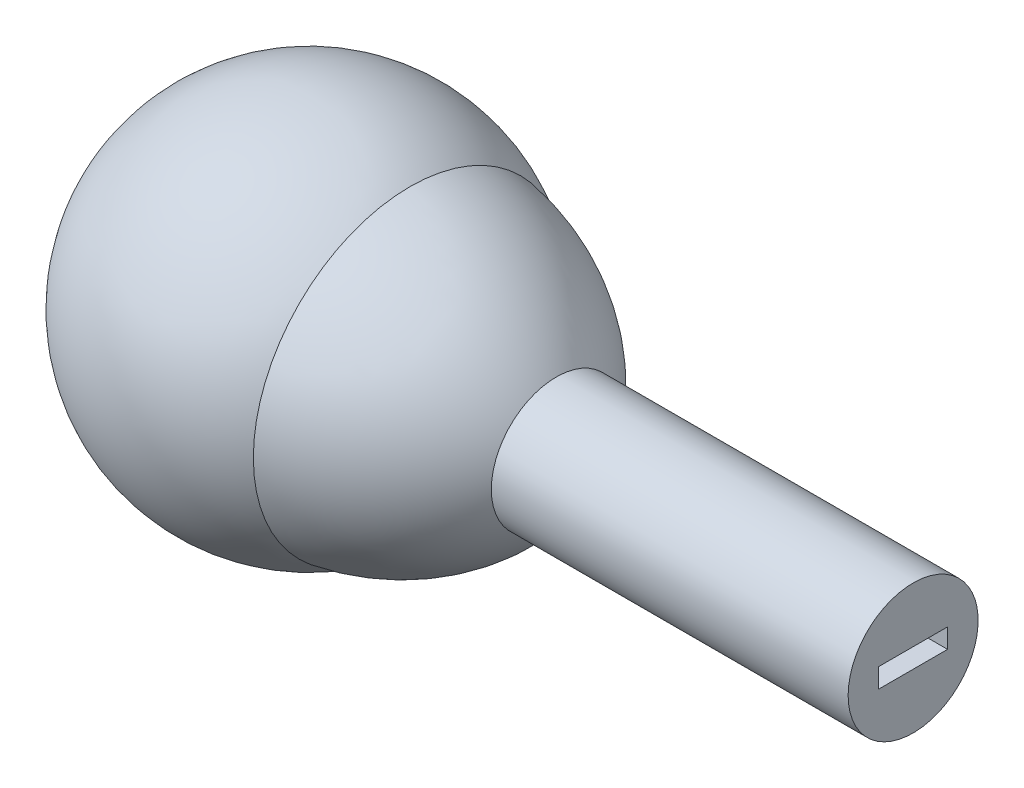
SolidWorks part; units mm, degrees
ref_plane "前视基准面" through (0, 0, 0) normal (0, 0, 1) x (1, 0, 0)
ref_plane "上视基准面" through (0, 0, 0) normal (0, 1, 0) x (1, 0, 0)
ref_plane "右视基准面" through (0, 0, 0) normal (1, 0, 0) x (0, 0, -1)
sketch "草图1" plane through (0, 0, 0) normal (0, 0, 1) x (1, 0, 0)
  line L0 (-28.1876, 0) -> (25, 0) construction
  line L1 (-2.4484, 5) -> (25, 5)
  line L6 (0, 0) -> (25, 5) construction
  line L10 (-35.7782, 0) -> (25, 0)
  line L11 (25, 5) -> (25, 0)
  arc A0 (-2.4484, 5) -> (-13.7088, 12.0461) centre (-16.5405, -5) ccw
  arc A1 (-13.7088, 12.0461) -> (-35.7782, 0) centre (-21.456, 0) ccw
  point P0 (0, 0)
  point P13 (15, 0)
  dimension "D5" = 16.5405
  dimension "D7" = 17.2797
  dimension "D6" = 14.3223
  dimension "D1" = 21.456
  dimension "D2" = 5
  dimension "D3" = 27.4484
  dimension "D4" = 5
revolve "旋转4" add sketch "草图1" angle 360 about L0
sketch "草图2" plane through (25, 0, 0) normal (1, 0, 0) x (0, 0, -1)
  line L1 (-2.65, -0.75) -> (2.65, -0.75)
  line L2 (-2.65, -0.75) -> (-2.65, 0.75)
  line L3 (-2.65, 0.75) -> (2.65, 0.75)
  line L4 (2.65, -0.75) -> (2.65, 0.75)
  line L5 (-2.65, -0.75) -> (2.65, 0.75) construction
  line L6 (-2.65, 0.75) -> (2.65, -0.75) construction
  point P0 (0, 0)
  dimension "D1" = 5.3
  dimension "D2" = 1.5
extrude "切除-拉伸2" cut sketch "草图2" against normal blind 12
